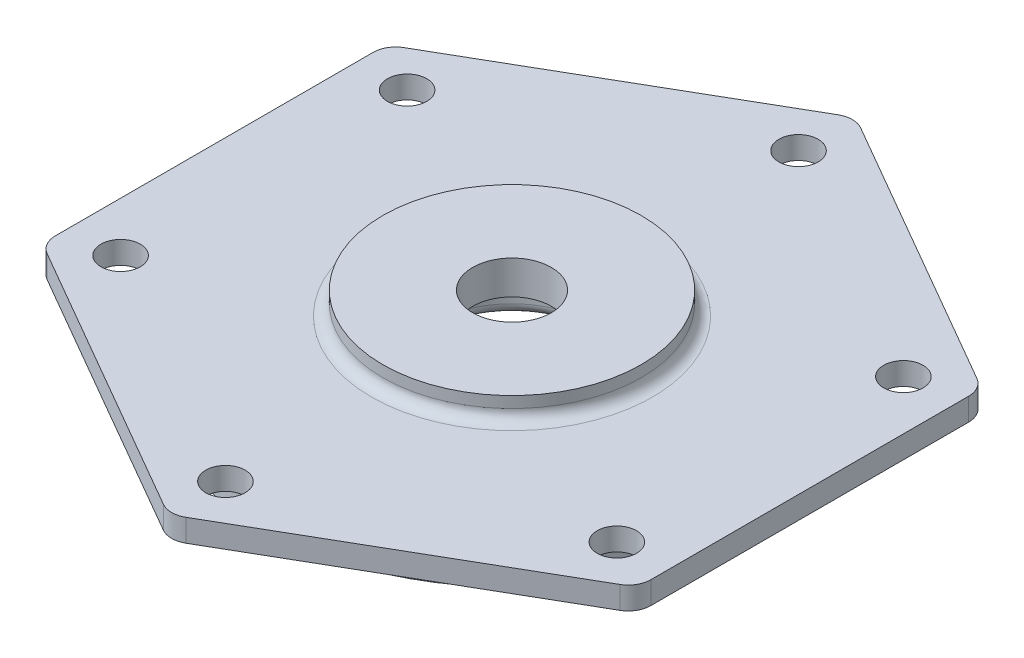
SolidWorks part; units mm, degrees
ref_plane "Front Plane" through (0, 0, 0) normal (0, 0, 1) x (1, 0, 0)
ref_plane "Top Plane" through (0, 0, 0) normal (0, 1, 0) x (1, 0, 0)
ref_plane "Right Plane" through (0, 0, 0) normal (1, 0, 0) x (0, 0, -1)
sketch "Sketch1" plane through (0, 0, 0) normal (0, 1, 0) x (1, 0, 0)
  line L1 (-51, -31.7543) -> (-2, -60.0444)
  line L2 (2, -60.0444) -> (51, -31.7543)
  line L3 (53, -28.2902) -> (53, 28.2902)
  line L4 (51, 31.7543) -> (2, 60.0444)
  line L5 (-2, 60.0444) -> (-51, 31.7543)
  line L6 (-53, 28.2902) -> (-53, -28.2902)
  circle A0 centre (0, 0) radius 53 construction
  arc A1 (-51, 31.7543) -> (-53, 28.2902) centre (-49, 28.2902) ccw
  arc A2 (2, 60.0444) -> (-2, 60.0444) centre (0, 56.5803) ccw
  arc A3 (53, 28.2902) -> (51, 31.7543) centre (49, 28.2902) ccw
  arc A4 (51, -31.7543) -> (53, -28.2902) centre (49, -28.2902) ccw
  arc A5 (-2, -60.0444) -> (2, -60.0444) centre (0, -56.5803) ccw
  arc A6 (-51, -31.7543) -> (-53, -28.2902) centre (-49, -28.2902) cw
  point P1 (0, 0)
  point P14 (0, 61.1991)
  dimension "D2" = 4
  dimension "D1" = 106
extrude "Boss-Extrude1" add sketch "Sketch1" along normal blind 4
sketch "Sketch2" plane through (0, 4, 0) normal (0, 1, 0) x (1, 0, 0)
  circle A0 centre (0, 0) radius 23
extrude "Boss-Extrude2" add sketch "Sketch2" along normal blind 4
sketch "Sketch3" plane through (0, 0, 0) normal (0, -1, 0) x (1, 0, 0)
  circle A0 centre (0, 0) radius 45
extrude "Boss-Extrude3" add sketch "Sketch3" along normal blind 6
sketch "Sketch4" plane through (0, -6, 0) normal (0, -1, 0) x (1, 0, 0)
  circle A0 centre (0, 0) radius 19
  circle A1 centre (0, 0) radius 40
  dimension "D1" = 80
  dimension "D2" = 38
extrude "Cut-Extrude1" cut sketch "Sketch4" against normal blind 6
sketch "Sketch5" plane through (0, -6, 0) normal (0, -1, 0) x (1, 0, 0)
  circle A0 centre (0, 0) radius 14
extrude "Cut-Extrude2" cut sketch "Sketch5" against normal blind 8
sketch "Sketch6" plane through (0, 2, 0) normal (0, -1, 0) x (1, 0, 0)
  circle A0 centre (0, 0) radius 7
extrude "Cut-Extrude3" cut sketch "Sketch6" against normal through all
fillet "Fillet1" radius 2 3 edges at (0, 4, 23) (0, -6, -40) (0, -6, -14)
sketch "Sketch7" plane through (0, 4, 0) normal (0, 1, 0) x (1, 0, 0)
  circle A0 centre (0, 0) radius 51 construction
  circle A1 centre (0, 51) radius 3.5
  circle A2 centre (44.1673, 25.5) radius 3.5
  circle A3 centre (44.1673, -25.5) radius 3.5
  circle A4 centre (0, -51) radius 3.5
  circle A5 centre (-44.1673, -25.5) radius 3.5
  circle A6 centre (-44.1673, 25.5) radius 3.5
  point P17 (0, 0)
  dimension "D1" = 102
  dimension "D2" = 6
extrude "Cut-Extrude4" cut sketch "Sketch7" against normal through all
